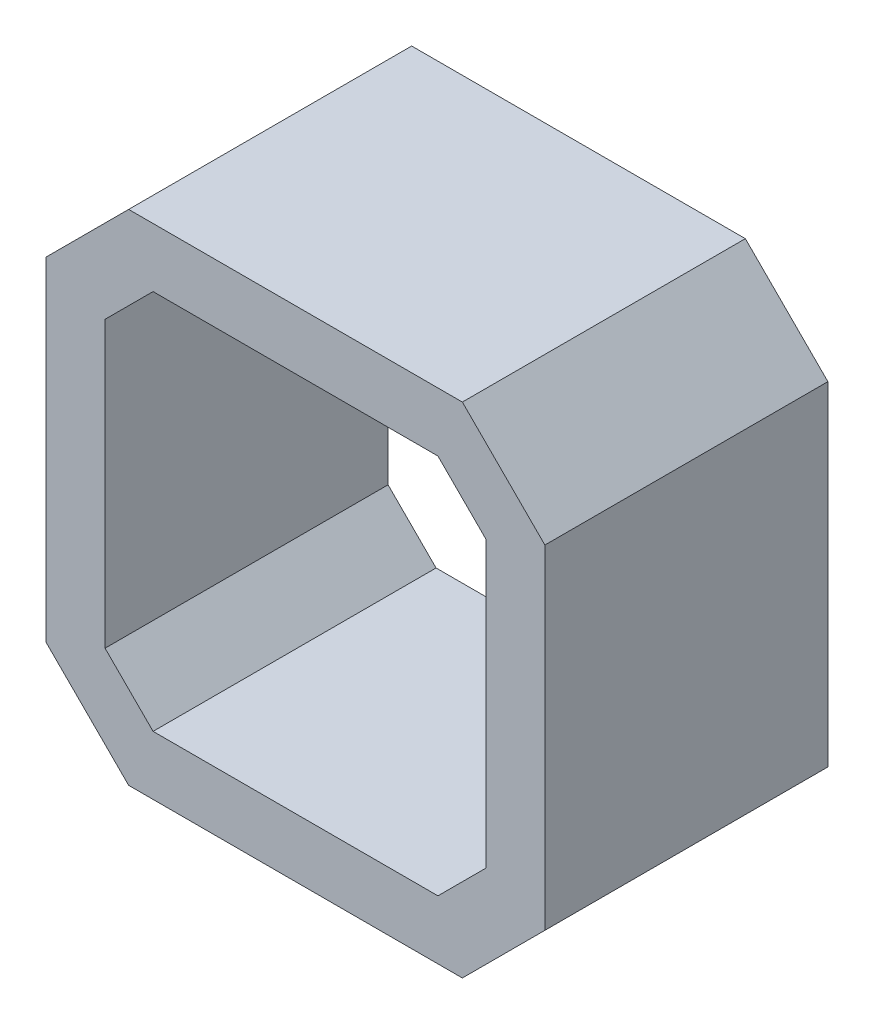
SolidWorks part; units mm, degrees
ref_plane "Front Plane" through (0, 0, 0) normal (0, 0, 1) x (1, 0, 0)
ref_plane "Top Plane" through (0, 0, 0) normal (0, 1, 0) x (1, 0, 0)
ref_plane "Right Plane" through (0, 0, 0) normal (1, 0, 0) x (0, 0, -1)
sketch "Sketch1" plane through (0, 0, 0) normal (0, 0, 1) x (1, 0, 0)
  line L0 (-21.15, 14.15) -> (-14.15, 21.15)
  line L1 (-14.15, -21.15) -> (14.15, -21.15)
  line L2 (-21.15, -14.15) -> (-21.15, 14.15)
  line L3 (-14.15, 21.15) -> (14.15, 21.15)
  line L4 (21.15, -14.15) -> (21.15, 14.15)
  line L5 (-21.15, -21.15) -> (21.15, 21.15) construction
  line L6 (-21.15, 21.15) -> (21.15, -21.15) construction
  line L7 (14.15, 21.15) -> (21.15, 14.15)
  line L8 (14.15, -21.15) -> (21.15, -14.15)
  line L9 (-21.15, -14.15) -> (-14.15, -21.15)
  line L10 (-12.0789, 16.15) -> (12.0789, 16.15)
  line L11 (12.0789, 16.15) -> (16.15, 12.0789)
  line L12 (16.15, -12.0789) -> (16.15, 12.0789)
  line L13 (12.0789, -16.15) -> (16.15, -12.0789)
  line L14 (-12.0789, -16.15) -> (12.0789, -16.15)
  line L15 (-16.15, -12.0789) -> (-12.0789, -16.15)
  line L16 (-16.15, -12.0789) -> (-16.15, 12.0789)
  line L17 (-16.15, 12.0789) -> (-12.0789, 16.15)
  point P0 (0, 0)
  dimension "D1" = 42.3
  dimension "D2" = 42.3
  dimension "D3" = 5
extrude "Boss-Extrude1" add sketch "Sketch1" along normal blind 24
scale "Scale1" scale about origin uniform scaling yes scale factor 3.5
